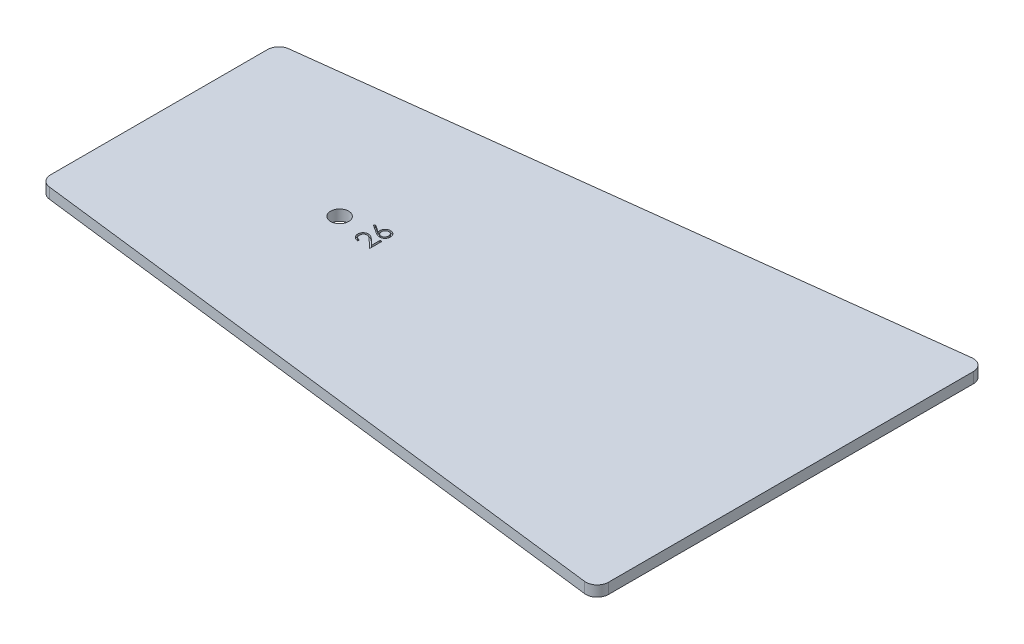
SolidWorks part; units mm, degrees
material "Acrylic (Medium-high impact)"
ref_plane "Front Plane" through (0, 0, 0) normal (0, 0, 1) x (1, 0, 0)
ref_plane "Top Plane" through (0, 0, 0) normal (0, 1, 0) x (1, 0, 0)
ref_plane "Right Plane" through (0, 0, 0) normal (1, 0, 0) x (0, 0, -1)
sketch "Sketch1" plane through (0, 0, 0) normal (0, 1, 0) x (1, 0, 0)
  line L0 (0, 0) -> (0, -355.6) construction
  line L1 (-66.675, 0) -> (66.675, 0)
  line L2 (66.675, 0) -> (109.8526, -355.6)
  line L3 (109.8526, -355.6) -> (-109.8526, -355.6)
  line L4 (-66.675, 0) -> (-109.8526, -355.6)
  dimension "D1" = 355.6
  dimension "D2" = 13.846
  dimension "D3" = 133.35
extrude "Boss-Extrude1" add sketch "Sketch1" along normal blind 5.9944
sketch "Sketch2" plane through (0, 5.9944, 0) normal (0, 1, 0) x (1, 0, 0)
  line L0 (0, 0) -> (0, -101.6) construction
  line L1 (66.675, 0) -> (-66.675, 0) construction
  circle A0 centre (0, -101.6) radius 5.08
  dimension "D2" = 10.16
  dimension "D1" = 101.6
extrude "Cut-Extrude1" cut sketch "Sketch2" against normal through all
sketch "Sketch3" plane through (0, 5.9944, 0) normal (0, 1, 0) x (1, 0, 0)
  line L2 (0, -101.6) -> (0, -114.3) construction
  line L3 (7.62, -125.73) -> (7.62, -114.3) construction
  line L4 (7.62, -125.73) -> (-7.62, -125.73) construction
  line L5 (7.62, -114.3) -> (-7.62, -114.3) construction
  line L6 (-7.62, -125.73) -> (-7.62, -114.3) construction
  line L7 (7.62, -125.73) -> (-7.62, -114.3) construction
  line L8 (7.62, -114.3) -> (-7.62, -125.73) construction
  text T0 "26\r\n" font "Century Gothic" height 10.16
  point P10 (0, -120.015)
  dimension "D3" = 12.7
  dimension "D4" = 15.24
  dimension "D5" = 11.43
extrude "Cut-Extrude2" cut sketch "Sketch3" against normal blind 1.27
fillet "Fillet1" radius 6.35 4 edges at (109.8526, 2.9972, 355.6) (-109.8526, 2.9972, 355.6) (66.675, 2.9972, 0) (-66.675, 2.9972, 0)
move or copy body "Body-Move/Copy1" bodies to move or copy 103 copy no rotation origin (0, 0, 177.8) rotation axis (0, 1, 0) rotation angle 90
